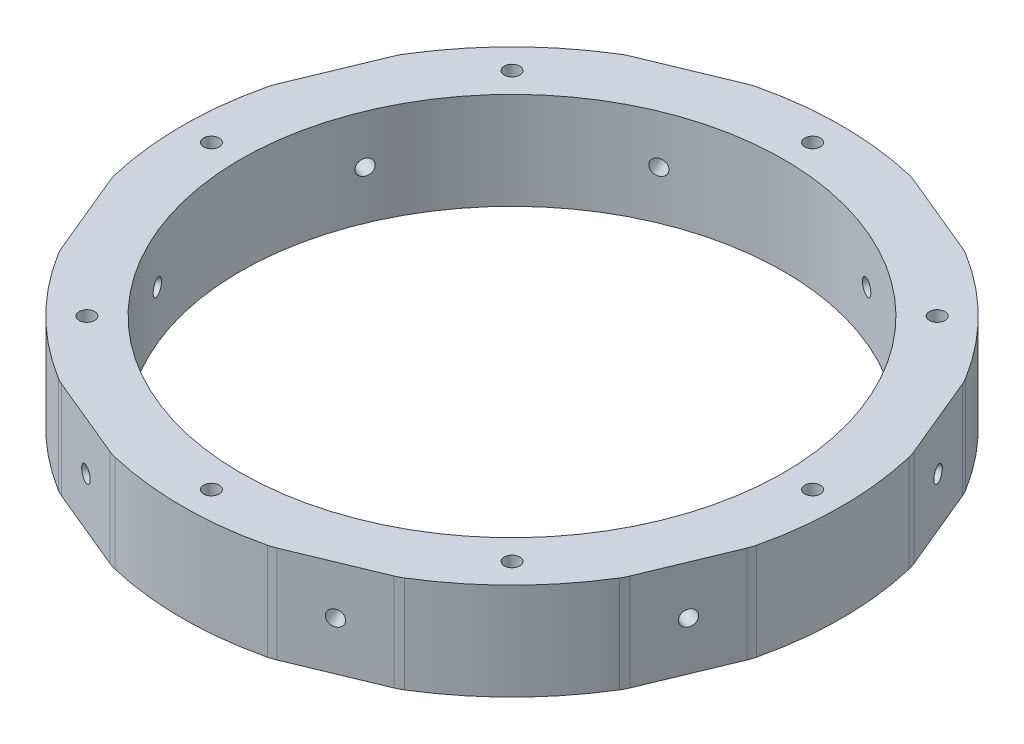
SolidWorks part; units mm, degrees
ref_plane "Front Plane" through (0, 0, 0) normal (0, 0, 1) x (1, 0, 0)
ref_plane "Top Plane" through (0, 0, 0) normal (0, 1, 0) x (1, 0, 0)
ref_plane "Right Plane" through (0, 0, 0) normal (1, 0, 0) x (0, 0, -1)
sketch "Sketch1" plane through (0, 0, 0) normal (0, 1, 0) x (1, 0, 0)
  circle A0 centre (0, 0) radius 56
  circle A1 centre (0, 0) radius 62 construction
  circle A2 centre (0, 0) radius 68
  circle A3 centre (0, 62) radius 1.6
  circle A4 centre (43.8406, 43.8406) radius 1.6
  circle A5 centre (62, 0) radius 1.6
  circle A6 centre (43.8406, -43.8406) radius 1.6
  circle A7 centre (0, -62) radius 1.6
  circle A8 centre (-43.8406, -43.8406) radius 1.6
  circle A9 centre (-62, 0) radius 1.6
  circle A10 centre (-43.8406, 43.8406) radius 1.6
  point P23 (0, 0)
  dimension "D1" = 112
  dimension "D2" = 6
  dimension "D3" = 6
  dimension "D4" = 3.2
  dimension "D5" = 8
extrude "Boss-Extrude1" add sketch "Sketch1" along normal blind 20
sketch "Sketch2" plane through (0, 20, 0) normal (0, 1, 0) x (1, 0, 0)
  line L0 (16.5008, 65.9676) -> (34.9783, 58.3139)
  line L1 (0, 62) -> (43.8406, 43.8406) construction
  line L2 (0, 68) -> (0, 0) construction
  line L3 (-16.5008, 65.9676) -> (-34.9783, 58.3139)
  line L4 (65.9676, 16.5008) -> (58.3139, 34.9783)
  line L5 (65.9676, -16.5008) -> (58.3139, -34.9783)
  line L6 (16.5008, -65.9676) -> (34.9783, -58.3139)
  line L7 (-16.5008, -65.9676) -> (-34.9783, -58.3139)
  line L8 (-65.9676, -16.5008) -> (-58.3139, -34.9783)
  line L9 (-65.9676, 16.5008) -> (-58.3139, 34.9783)
  circle A0 centre (0, 0) radius 68 construction
  arc A1 (16.5008, 65.9676) -> (-16.5008, 65.9676) centre (0, 0) ccw
  arc A2 (65.9676, -16.5008) -> (65.9676, 16.5008) centre (0, 0) ccw
  arc A3 (-16.5008, -65.9676) -> (16.5008, -65.9676) centre (0, 0) ccw
  arc A4 (-65.9676, 16.5008) -> (-65.9676, -16.5008) centre (0, 0) ccw
  arc A5 (-58.3139, 34.9783) -> (-34.9783, 58.3139) centre (0, 0) cw
  arc A6 (-58.3139, -34.9783) -> (-34.9783, -58.3139) centre (0, 0) ccw
  arc A7 (34.9783, -58.3139) -> (58.3139, -34.9783) centre (0, 0) ccw
  arc A8 (34.9783, 58.3139) -> (58.3139, 34.9783) centre (0, 0) cw
  circle A9 centre (0, 0) radius 76
  point P28 (0, 0)
  dimension "D3" = 8
  dimension "D1" = 20
  dimension "D2" = 4
extrude "Cut-Extrude1" cut sketch "Sketch2" against normal through all
sketch "Sketch3" plane through (-25.7396, 0, -62.1408) normal (-0.3827, 0, -0.9239) x (-0.9239, 0, 0.3827)
  line L0 (-10, 20) -> (10, 0) construction
  line L1 (-10, 0) -> (10, 20) construction
  circle A0 centre (0, 10) radius 1.6
  point P10 (0, 10)
  dimension "D1" = 3.2
extrude "Cut-Extrude2" cut sketch "Sketch3" against normal up to surface (11.2835 mm away)
pattern_circular "CirPattern4" count 8 over 360 about axis through (0, 20, 0) along (0, 1, 0) of "Cut-Extrude2"
fillet "Fillet1" radius 10 16 edges at (58.3139, 10, 34.9783) (65.9676, 10, 16.5008) (16.5008, 10, 65.9676) (34.9783, 10, 58.3139) (-34.9783, 10, 58.3139) (-16.5008, 10, 65.9676) (-65.9676, 10, 16.5008) (-58.3139, 10, 34.9783) (-58.3139, 10, -34.9783) (-65.9676, 10, -16.5008) (-16.5008, 10, -65.9676) (-34.9783, 10, -58.3139) (34.9783, 10, -58.3139) (16.5008, 10, -65.9676) (65.9676, 10, -16.5008) (58.3139, 10, -34.9783)
